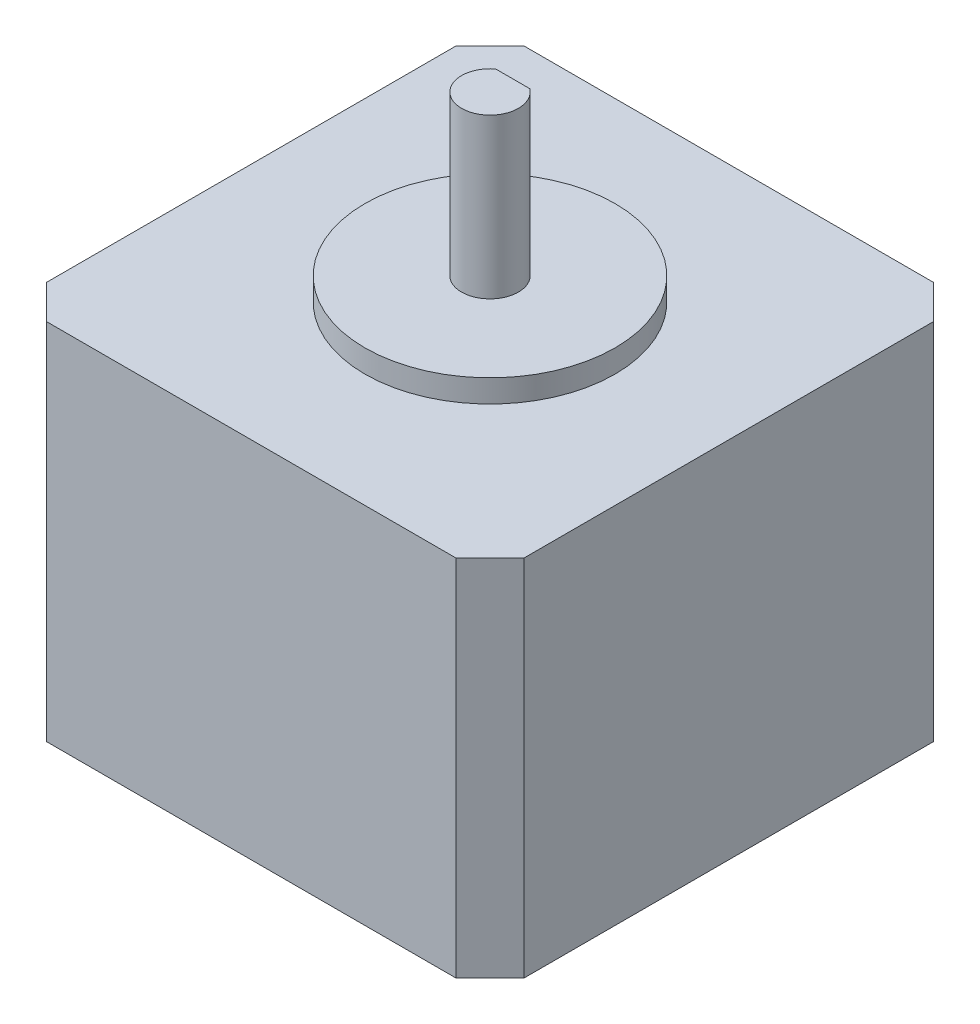
SolidWorks part; units mm, degrees
material "ABS PC"
ref_plane "Front Plane" through (0, 0, 0) normal (0, 0, 1) x (1, 0, 0)
ref_plane "Top Plane" through (0, 0, 0) normal (0, 1, 0) x (1, 0, 0)
ref_plane "Right Plane" through (0, 0, 0) normal (1, 0, 0) x (0, 0, -1)
sketch "Sketch1" plane through (0, 0, 0) normal (0, 1, 0) x (1, 0, 0)
  line L0 (-18, 21) -> (-21, 18)
  line L1 (-18, -21) -> (18, -21)
  line L2 (-21, -18) -> (-21, 18)
  line L3 (-18, 21) -> (18, 21)
  line L4 (21, -18) -> (21, 18)
  line L5 (-19.5, -19.5) -> (19.5, 19.5) construction
  line L6 (-21, 21) -> (19.5, -19.5) construction
  line L7 (21, 18) -> (18, 21)
  line L8 (18, -21) -> (21, -18)
  line L9 (-21, -18) -> (-18, -21)
  point P0 (0, 0)
  point P17 (0, 0)
  dimension "D3" = 3
  dimension "D4" = 3
  dimension "D5" = 4
extrude "Boss-Extrude1" add sketch "Sketch1" along normal blind 32
sketch "Sketch2" plane through (0, 32, 0) normal (0, 1, 0) x (1, 0, 0)
  circle A0 centre (0, 0) radius 11
  dimension "D1" = 22
extrude "Boss-Extrude2" add sketch "Sketch2" along normal blind 2
sketch "Sketch3" plane through (0, 34, 0) normal (0, 1, 0) x (1, 0, 0)
  line L0 (-1.5, 2) -> (1.5, 2)
  arc A0 (-1.5, 2) -> (1.5, 2) centre (0, 0) ccw
  dimension "D1" = 5
  dimension "D2" = 2
extrude "Boss-Extrude3" add sketch "Sketch3" along normal blind 14
